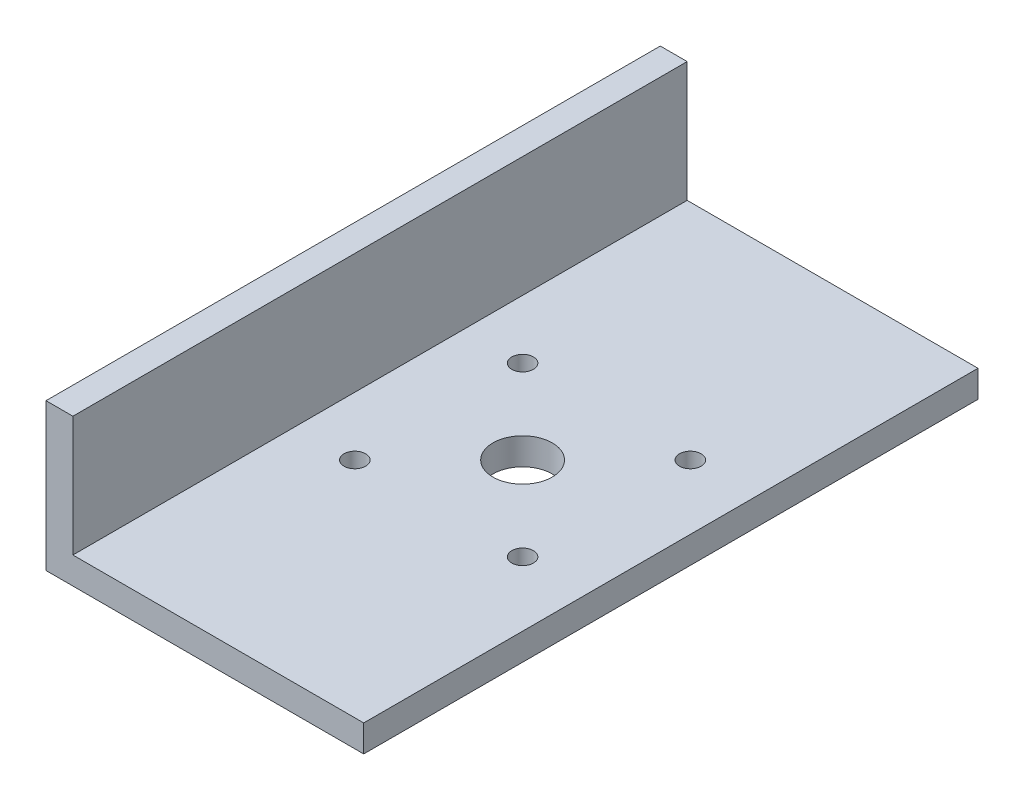
SolidWorks part; units mm, degrees
ref_plane "Front Plane" through (0, 0, 0) normal (0, 0, 1) x (1, 0, 0)
ref_plane "Top Plane" through (0, 0, 0) normal (0, 1, 0) x (1, 0, 0)
ref_plane "Right Plane" through (0, 0, 0) normal (1, 0, 0) x (0, 0, -1)
sketch "Sketch1" plane through (0, 0, 0) normal (0, 0, 1) x (1, 0, 0)
  line L0 (0, -37.5) -> (0, 37.5)
  line L1 (0, 37.5) -> (75, 37.5)
  line L2 (75, 37.5) -> (75, 31.15)
  line L3 (75, 31.15) -> (6.35, 31.15)
  line L4 (6.35, 31.15) -> (6.35, -31.15)
  line L5 (6.35, -31.15) -> (75, -31.15)
  line L6 (75, -31.15) -> (75, -37.5)
  line L7 (75, -37.5) -> (0, -37.5)
  line L8 (0, 0) -> (6.35, 0) construction
  dimension "D1" = 75
  dimension "D2" = 75
  dimension "D3" = 6.35
extrude "Boss-Extrude1" add sketch "Sketch1" along normal blind 145
sketch "Sketch2" plane through (0, 37.5, 0) normal (0, 1, 0) x (1, 0, 0)
  line L0 (40, -72.5) -> (0, -72.5) construction
  line L1 (0, -145) -> (0, 0) construction
  line L6 (75, 0) -> (6.35, 0)
  line L7 (75, -145) -> (75, 0)
  line L8 (6.35, -145) -> (75, -145)
  line L9 (6.35, 0) -> (6.35, -145)
  line L10 (75, 0) -> (6.35, 0)
  line L11 (75, -145) -> (75, 0)
  line L12 (6.35, -145) -> (75, -145)
  line L13 (6.35, 0) -> (6.35, -145)
  dimension "D2" = 0
  dimension "D1" = 40
extrude "Cut-Extrude1" cut sketch "Sketch2" against normal blind 10
sketch "Sketch3" plane through (0, -37.5, 0) normal (0, -1, 0) x (1, 0, 0)
  circle A0 centre (40, 72.5) radius 7
  circle A1 centre (40, 72.5) radius 27.5 construction
  dimension "D1" = 14
extrude "Cut-Extrude2" cut sketch "Sketch3" against normal blind 10
sketch "Sketch4" plane through (0, -31.15, 0) normal (0, 1, 0) x (1, 0, 0)
  line L0 (59.799, -92.299) -> (59.799, -52.701) construction
  line L1 (59.799, -52.701) -> (20.201, -52.701) construction
  circle A0 centre (59.799, -52.701) radius 2.55
  circle A1 centre (59.799, -92.299) radius 2.55
  circle A2 centre (20.201, -92.299) radius 2.55
  circle A3 centre (20.201, -52.701) radius 2.55
  circle A4 centre (40, -72.5) radius 28 construction
  dimension "D1" = 5.1
  dimension "D2" = 56
extrude "Cut-Extrude3" cut sketch "Sketch4" against normal blind 10
sketch "Sketch5" plane through (6.35, 0, 0) normal (1, 0, 0) x (0, 0, -1)
  line L0 (110.0591, 58.6923) -> (-168.5596, 58.6923)
  line L1 (110.0591, 58.6923) -> (110.0591, -2.7755)
  line L2 (-168.5596, 58.6923) -> (-168.5596, -2.7755)
  line L3 (110.0591, -2.7755) -> (-168.5596, -2.7755)
  line L4 (110.0591, 58.6923) -> (-168.5596, -2.7755) construction
  line L5 (-168.5596, 58.6923) -> (110.0591, -2.7755) construction
  point P1 (-29.2502, 27.9584)
extrude "Cut-Extrude4" cut sketch "Sketch5" against normal blind 10
